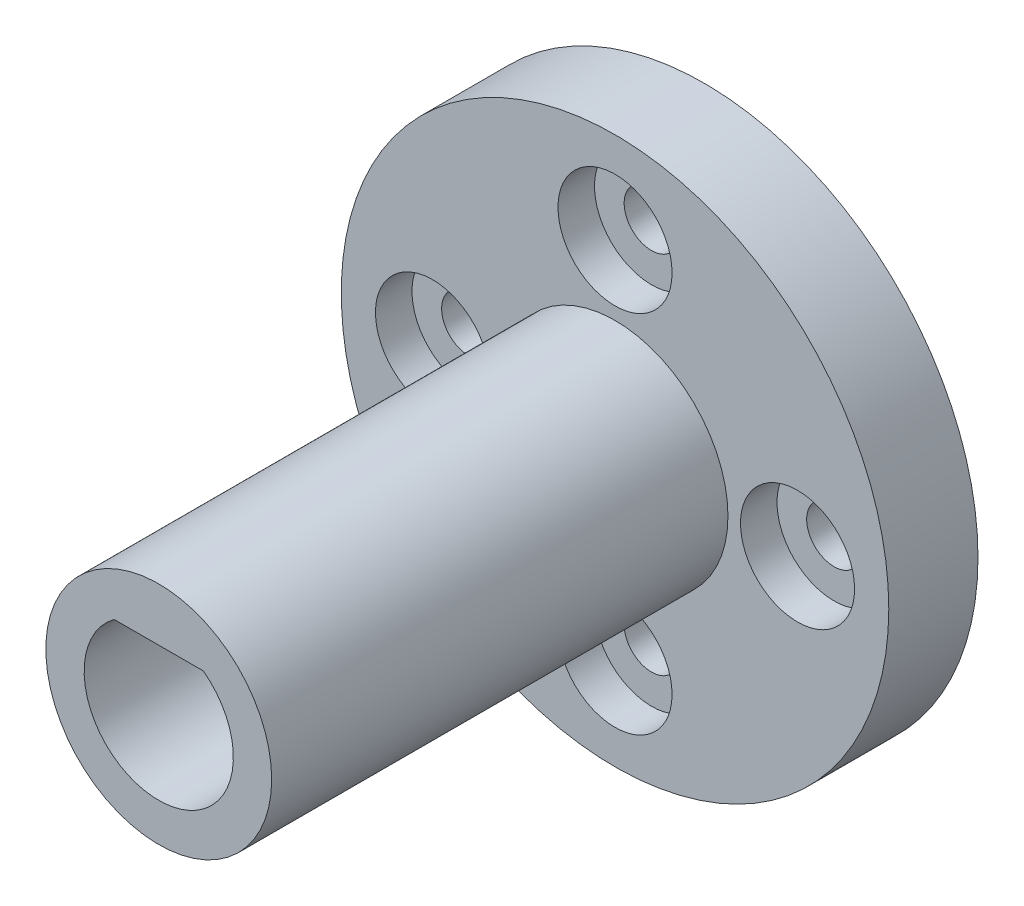
SolidWorks part; units mm, degrees
ref_plane "Plan de face" through (0, 0, 0) normal (0, 0, 1) x (1, 0, 0)
ref_plane "Plan de dessus" through (0, 0, 0) normal (0, 1, 0) x (1, 0, 0)
ref_plane "Plan de droite" through (0, 0, 0) normal (1, 0, 0) x (0, 0, -1)
sketch "Esquisse1" plane through (0, 0, 0) normal (0, 0, 1) x (1, 0, 0)
  circle A0 centre (0, 0) radius 12
  dimension "D1" = 24
extrude "Boss.-Extru.1" add sketch "Esquisse1" along normal blind 3.91
sketch "Esquisse6" plane through (0, 0, 0) normal (0, 0, -1) x (-1, 0, 0)
  circle A0 centre (0, 0) radius 4.125
  dimension "D1" = 8.25
extrude "Enlèv. mat.-Extru.2" cut sketch "Esquisse6" against normal blind 2
sketch "Esquisse7" plane through (0, 0, 3.91) normal (0, 0, 1) x (1, 0, 0)
  line L0 (1.9567, 2.62) -> (-1.9567, 2.62)
  line L1 (-5.4714, -3.27) -> (6.192, -3.27) construction
  arc A0 (-1.9567, 2.62) -> (1.9567, 2.62) centre (0, 0) ccw
  circle A1 centre (0, 0) radius 4.95
  dimension "D1" = 6.54
  dimension "D3" = 9.9
  dimension "D2" = 5.89
extrude "Boss.-Extru.2" add sketch "Esquisse7" along normal blind 20 contours A1 L1 A0 L0 | L1 A1
hole_wizard "Chambrage pour vis à tête ronde bombée M21" positions "Esquisse10" profile "Esquisse11" counterbore size "M2" standard "Ansi Metric" end condition through all
sketch "Esquisse10" plane through (0, 0, 3.91) normal (0, 0, 1) x (1, 0, 0)
  point P0 (0, 8)
  dimension "D1" = 8
sketch "Esquisse11" plane through (0, 8, 3.91) normal (1, 0, 0) x (0, -1, 0)
  line L0 (0, 0) -> (0, 3.91)
  line L1 (0, 3.91) -> (1.2, 3.91)
  line L3 (1.2, 3.91) -> (1.2, 1.6)
  line L4 (1.2, 1.6) -> (2.5, 1.6)
  line L5 (2.5, 1.6) -> (2.5, 0)
  line L7 (2.5, 0) -> (0, 0)
  line L11 (0, -6.35) -> (0, 107.95) construction
  dimension "Diamètre du perçage jusqu'au prochain" = 2.4
  dimension "Profondeur du perçage jusqu'au prochain" = 3.91
  dimension "Diamètre du chambrage" = 5
  dimension "Profondeur du chambrage" = 1.6
pattern_circular "Répétition circulaire2" count 4 every 90 about axis through (0, 0, 0) along (0, 0, 1) of "Chambrage pour vis à tête ronde bombée M21"
